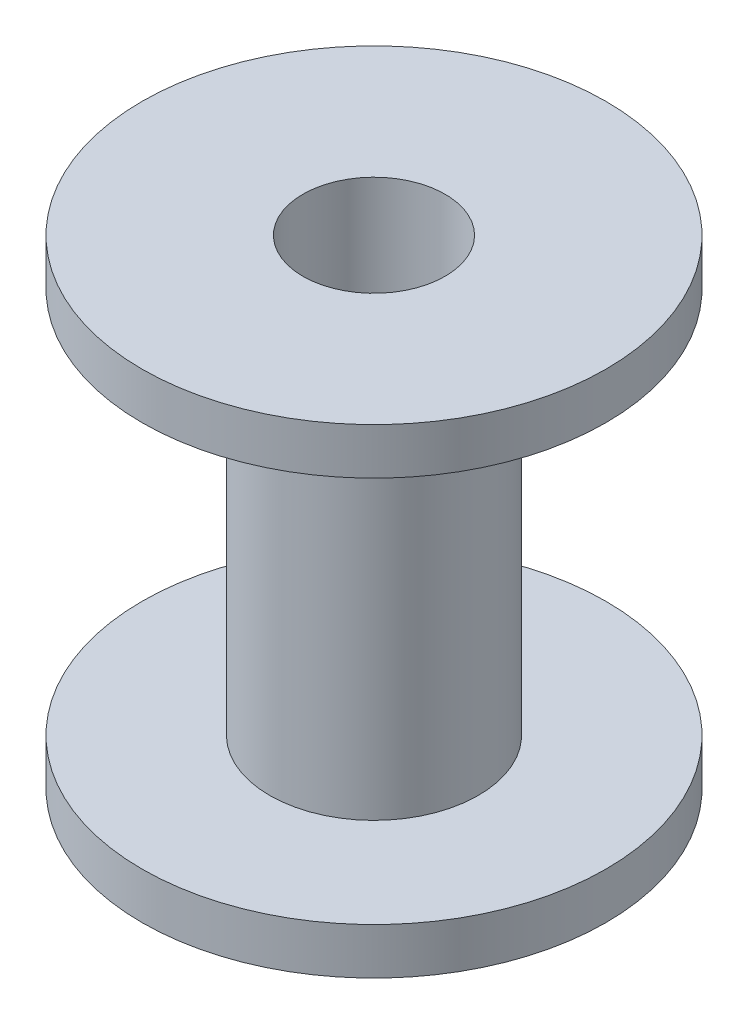
SolidWorks part; units mm, degrees
ref_plane "Front Plane" through (0, 0, 0) normal (0, 0, 1) x (1, 0, 0)
ref_plane "Top Plane" through (0, 0, 0) normal (0, 1, 0) x (1, 0, 0)
ref_plane "Right Plane" through (0, 0, 0) normal (1, 0, 0) x (0, 0, -1)
sketch "Sketch2" plane through (0, 0, 0) normal (1, 0, 0) x (0, 0, -1)
  line L0 (0, 15.5) -> (0, -9.6242) construction
  line L1 (-15, 15.5) -> (-15, 12.5)
  line L2 (-15, 12.5) -> (-6.75, 12.5)
  line L3 (-6.75, 12.5) -> (-6.75, -12.5)
  line L4 (0, 0) -> (-6.75, 0) construction
  line L5 (-15, 15.5) -> (-4.6, 15.5)
  line L6 (-15, -12.5) -> (-6.75, -12.5)
  line L7 (-15, -15.5) -> (-15, -12.5)
  line L16 (-4.6, 15.5) -> (-4.6, -15.5)
  line L20 (-15, -15.5) -> (-4.6, -15.5)
  point P13 (0, -15.5)
  dimension "D2" = 13.5
  dimension "D3" = 3
  dimension "D4" = 25
  dimension "D5" = 9.2
  dimension "D7" = 30
  dimension "D8" = 8.25
revolve "Revolve1" add sketch "Sketch2" angle 360 about L0
